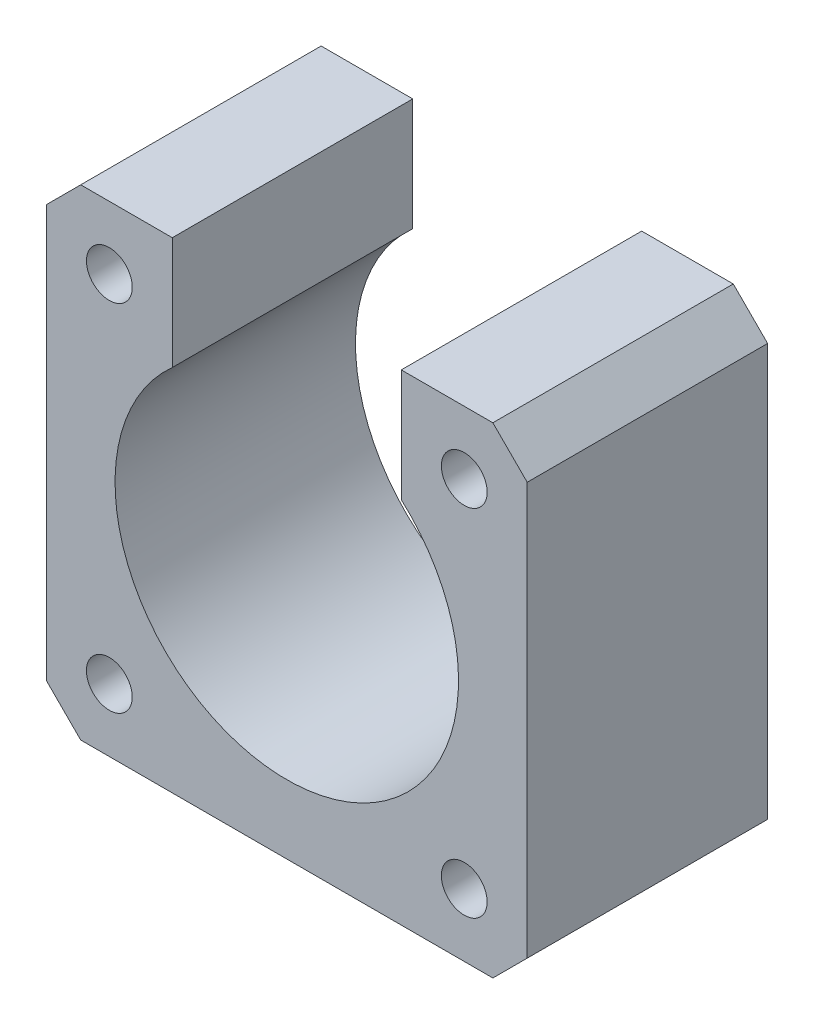
SolidWorks part; units mm, degrees
ref_plane "前视基准面" through (0, 0, 0) normal (0, 0, 1) x (1, 0, 0)
ref_plane "上视基准面" through (0, 0, 0) normal (0, 1, 0) x (1, 0, 0)
ref_plane "右视基准面" through (0, 0, 0) normal (1, 0, 0) x (0, 0, -1)
sketch "草图1" plane through (0, 0, 0) normal (0, 0, 1) x (1, 0, 0)
  line L0 (-21, 18) -> (-18, 21)
  line L1 (-18, -21) -> (18, -21)
  line L2 (-21, -18) -> (-21, 18)
  line L3 (-18, 21) -> (-10, 21)
  line L4 (21, -18) -> (21, 18)
  line L5 (-21, -21) -> (21, 21) construction
  line L6 (-21, 21) -> (21, -21) construction
  line L7 (-21, -18) -> (-18, -21)
  line L8 (18, -21) -> (21, -18)
  line L9 (18, 21) -> (21, 18)
  line L10 (-10, 21) -> (-10, 11.1803)
  line L11 (10, 21) -> (10, 11.1803)
  line L12 (10, 21) -> (18, 21)
  arc A0 (-10, 11.1803) -> (10, 11.1803) centre (0, 0) ccw
  circle A1 centre (15.5, 15.5) radius 2
  circle A2 centre (15.5, -15.5) radius 2
  circle A3 centre (-15.5, -15.5) radius 2
  circle A4 centre (-15.5, 15.5) radius 2
  point P0 (0, 0)
  point P18 (0, 0)
  dimension "D3" = 30
  dimension "D4" = 4
  dimension "D1" = 42
  dimension "D2" = 42
  dimension "D6" = 31
  dimension "D7" = 20
  dimension "D5" = 4
extrude "凸台-拉伸1" add sketch "草图1" along normal blind 21
